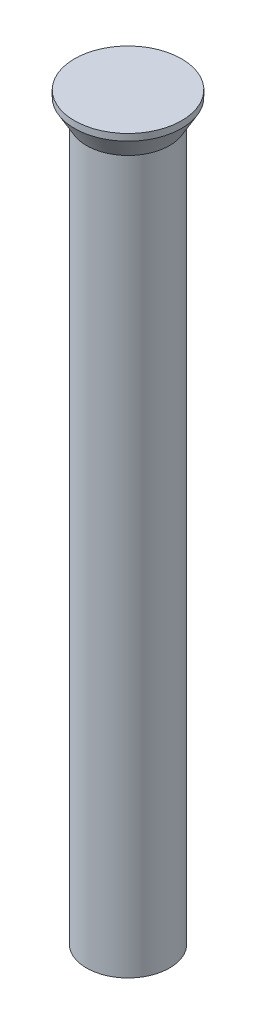
SolidWorks part; units mm, degrees
material "M2 HSS"
ref_plane "Front Plane" through (0, 0, 0) normal (0, 0, 1) x (1, 0, 0)
ref_plane "Top Plane" through (0, 0, 0) normal (0, 1, 0) x (1, 0, 0)
ref_plane "Right Plane" through (0, 0, 0) normal (1, 0, 0) x (0, 0, -1)
sketch "Sketch1" plane through (0, 0, 0) normal (0, 0, 1) x (1, 0, 0)
  line L0 (0, 0) -> (4, 0)
  line L1 (4, 0) -> (4, -0.5)
  line L2 (4, -0.5) -> (3.1, -2.0588)
  line L3 (3.1, -2.0588) -> (3.1, -55.2)
  line L4 (3.1, -55.2) -> (0, -55.2)
  line L5 (0, -55.2) -> (0, 0)
  line L6 (0, -60.2) -> (0, 5) construction
  dimension "D1" = 5
  dimension "D2" = 5
  dimension "D3" = 0.5
  dimension "D4" = 30
  dimension "D5" = 6.2
  dimension "D6" = 8
  dimension "D7" = 55.2
revolve "Revolve1" add sketch "Sketch1" angle 360 about L6
